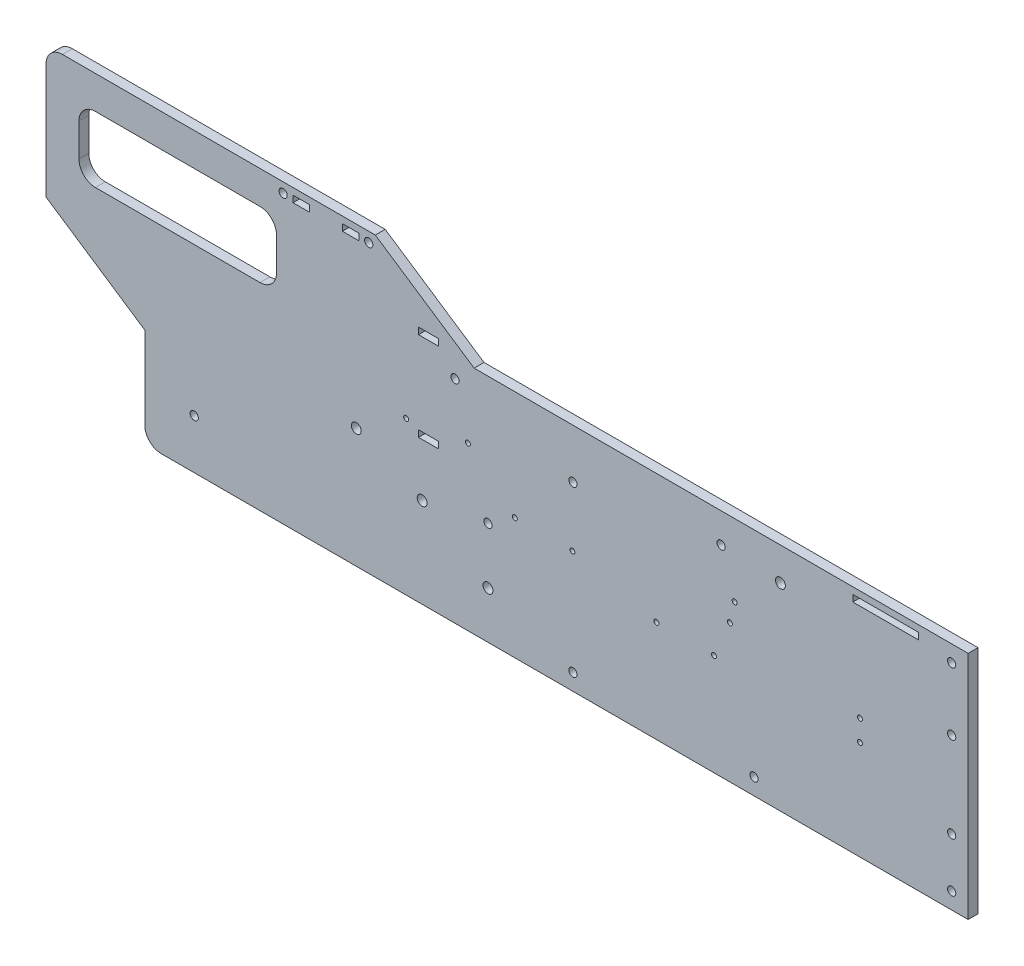
SolidWorks part; units mm, degrees
ref_plane "Front Plane" through (0, 0, 0) normal (0, 0, 1) x (1, 0, 0)
ref_plane "Top Plane" through (0, 0, 0) normal (0, 1, 0) x (1, 0, 0)
ref_plane "Right Plane" through (0, 0, 0) normal (1, 0, 0) x (0, 0, -1)
sketch "Sketch1" plane through (0, 0, 0) normal (0, 0, 1) x (1, 0, 0)
  line L0 (-211.6542, 23.1199) -> (-151.6542, 23.1199)
  line L1 (58.3458, 13.1199) -> (58.3458, -56.8801)
  line L2 (-121.6542, 33.1199) -> (-221.6542, 33.1199)
  line L3 (-221.6542, 33.1199) -> (-221.6542, -6.8801)
  line L4 (-191.6542, -56.8801) -> (58.3458, -56.8801)
  line L5 (-121.6542, 33.1199) -> (-91.6542, 13.1199)
  line L6 (-191.6542, -26.8801) -> (-191.6542, -56.8801)
  line L7 (-91.6542, 13.1199) -> (58.3458, 13.1199)
  line L8 (-211.6542, 3.1199) -> (-151.6542, 3.1199)
  line L9 (-151.6542, 3.1199) -> (-151.6542, 23.1199)
  line L10 (-211.6542, 23.1199) -> (-211.6542, 3.1199)
  line L12 (28.3458, 11.1199) -> (28.3458, 10.1199)
  line L13 (-221.6542, -6.8801) -> (-191.6542, -26.8801)
  line L14 (43.3458, 11.1199) -> (38.3458, 11.1199)
  line L15 (38.3458, 11.1199) -> (38.3458, 10.1199)
  line L16 (38.3458, 10.1199) -> (43.3458, 10.1199)
  line L17 (43.3458, 10.1199) -> (43.3458, 11.1199)
  line L18 (28.3458, 10.1199) -> (23.3458, 10.1199)
  line L19 (23.3458, 10.1199) -> (23.3458, 11.1199)
  line L20 (23.3458, 11.1199) -> (28.3458, 11.1199)
  circle A0 centre (53.3458, 7.9455) radius 1.25
  circle A1 centre (53.3458, -52.0545) radius 1.25
  circle A2 centre (25.5058, -18.3301) radius 0.75
extrude "Boss-Extrude2" add sketch "Sketch1" along normal blind 3
sketch "Sketch4" plane through (0, 0, 3) normal (0, 0, 1) x (1, 0, 0)
  circle A0 centre (-12.5542, -8.7801) radius 0.75
extrude "Cut-Extrude3" cut sketch "Sketch4" against normal blind 3
sketch "Sketch5" plane through (0, 0, 3) normal (0, 0, 1) x (1, 0, 0)
  circle A0 centre (-13.9942, -15.0201) radius 0.75
extrude "Cut-Extrude4" cut sketch "Sketch5" against normal blind 3
sketch "Sketch14" plane through (0, 0, 3) normal (0, 0, 1) x (1, 0, 0)
  circle A0 centre (25.5058, -20.3301) radius 0.75
  circle A1 centre (25.5058, -26.7301) radius 0.75
extrude "Cut-Extrude12" cut sketch "Sketch14" against normal blind 10
sketch "Sketch15" plane through (0, 0, 3) normal (0, 0, 1) x (1, 0, 0)
  circle A0 centre (25.5058, -18.3301) radius 0.75
extrude "Boss-Extrude4" add sketch "Sketch15" against normal blind 3
sketch "Sketch20" plane through (0, 0, 3) normal (0, 0, 1) x (1, 0, 0)
  circle A0 centre (-16.6542, 4.1199) radius 1.25
extrude "Cut-Extrude17" cut sketch "Sketch20" against normal blind 3
sketch "Sketch23" plane through (0, 0, 3) normal (0, 0, 1) x (1, 0, 0)
  circle A0 centre (-93.5247, -7.5214) radius 0.75
extrude "Cut-Extrude21" cut sketch "Sketch23" against normal blind 10
sketch "Sketch25" plane through (0, 0, 3) normal (0, 0, 1) x (1, 0, 0)
  line L0 (28.3458, 11.1199) -> (38.3458, 11.1199)
  line L1 (38.3458, 11.1199) -> (38.3458, 10.1199)
  line L2 (38.3458, 10.1199) -> (28.3458, 10.1199)
  line L3 (28.3458, 10.1199) -> (28.3458, 11.1199)
extrude "Cut-Extrude23" cut sketch "Sketch25" against normal blind 3
sketch "Sketch26" plane through (0, 0, 3) normal (0, 0, 1) x (1, 0, 0)
  circle A0 centre (-97.4442, 7.4199) radius 1.25
extrude "Cut-Extrude24" cut sketch "Sketch26" against normal blind 3
sketch "Sketch29" plane through (0, 0, 3) normal (0, 0, 1) x (1, 0, 0)
  circle A0 centre (-176.6542, -41.8801) radius 1.25
extrude "Cut-Extrude27" cut sketch "Sketch29" against normal blind 3
sketch "Sketch33" plane through (0, 0, 3) normal (0, 0, 1) x (1, 0, 0)
  line L3 (-126.6542, 31.1199) -> (-131.6542, 31.1199)
  line L4 (-131.6542, 31.1199) -> (-131.6542, 29.1199)
  line L5 (-131.6542, 29.1199) -> (-126.6542, 29.1199)
  line L6 (-126.6542, 29.1199) -> (-126.6542, 31.1199)
extrude "Cut-Extrude31" cut sketch "Sketch33" against normal blind 3
sketch "Sketch34" plane through (0, 0, 3) normal (0, 0, 1) x (1, 0, 0)
  line L0 (-146.6542, 31.1199) -> (-141.6542, 31.1199)
  line L1 (-146.6542, 31.1199) -> (-146.6542, 29.1199)
  line L2 (-146.6542, 29.1199) -> (-141.6542, 29.1199)
  line L3 (-141.6542, 29.1199) -> (-141.6542, 31.1199)
extrude "Cut-Extrude32" cut sketch "Sketch34" against normal blind 3
sketch "Sketch35" plane through (0, 0, 3) normal (0, 0, 1) x (1, 0, 0)
  circle A0 centre (-123.6542, 30.1199) radius 1.25
  circle A1 centre (-149.6542, 30.1199) radius 1.25
extrude "Cut-Extrude33" cut sketch "Sketch35" against normal blind 3
sketch "Sketch37" plane through (0, 0, 3) normal (0, 0, 1) x (1, 0, 0)
  circle A0 centre (-61.6542, -1.8801) radius 1.25
extrude "Cut-Extrude34" cut sketch "Sketch37" against normal blind 3
sketch "Sketch38" plane through (0, 0, 3) normal (0, 0, 1) x (1, 0, 0)
  circle A0 centre (-87.4442, -25.5801) radius 1.25
extrude "Cut-Extrude35" cut sketch "Sketch38" against normal blind 3
sketch "Sketch41" plane through (0, 0, 3) normal (0, 0, 1) x (1, 0, 0)
  circle A0 centre (-112.3061, -10.3951) radius 0.75
extrude "Cut-Extrude38" cut sketch "Sketch41" against normal blind 3
sketch "Sketch42" plane through (0, 0, 3) normal (0, 0, 1) x (1, 0, 0)
  line L0 (-108.5247, -11.5214) -> (-108.5247, -13.5214)
  line L1 (-108.5247, -13.5214) -> (-102.5247, -13.5214)
  line L2 (-102.5247, -13.5214) -> (-102.5247, -11.5214)
  line L3 (-102.5247, -11.5214) -> (-108.5247, -11.5214)
extrude "Cut-Extrude40" cut sketch "Sketch42" against normal blind 3
sketch "Sketch43" plane through (0, 0, 3) normal (0, 0, 1) x (1, 0, 0)
  line L0 (-108.5247, 15.4786) -> (-108.5247, 13.4786)
  line L1 (-108.5247, 15.4786) -> (-102.5247, 15.4786)
  line L2 (-102.5247, 15.4786) -> (-102.5247, 13.4786)
  line L3 (-102.5247, 13.4786) -> (-108.5247, 13.4786)
extrude "Cut-Extrude41" cut sketch "Sketch43" against normal blind 3
sketch "Sketch45" plane through (0, 0, 3) normal (0, 0, 1) x (1, 0, 0)
  circle A0 centre (53.3458, -52.0545) radius 1.25
extrude "Boss-Extrude5" add sketch "Sketch45" against normal blind 3
sketch "Sketch46" plane through (0, 0, 3) normal (0, 0, 1) x (1, 0, 0)
  circle A0 centre (53.3458, 7.9455) radius 1.25
extrude "Boss-Extrude6" add sketch "Sketch46" against normal blind 3
sketch "Sketch47" plane through (0, 0, 3) normal (0, 0, 1) x (1, 0, 0)
  circle A0 centre (53.3458, 8.1199) radius 1.25
extrude "Cut-Extrude42" cut sketch "Sketch47" against normal blind 3
sketch "Sketch49" plane through (0, 0, 3) normal (0, 0, 1) x (1, 0, 0)
  circle A0 centre (53.3458, -10.8801) radius 1.25
extrude "Cut-Extrude43" cut sketch "Sketch49" against normal blind 3
sketch "Sketch51" plane through (0, 0, 3) normal (0, 0, 1) x (1, 0, 0)
  circle A0 centre (53.3458, -36.8801) radius 1.25
extrude "Cut-Extrude44" cut sketch "Sketch51" against normal blind 3
sketch "Sketch52" plane through (0, 0, 3) normal (0, 0, 1) x (1, 0, 0)
  circle A0 centre (53.3458, -51.8801) radius 1.25
extrude "Cut-Extrude45" cut sketch "Sketch52" against normal blind 3
sketch "Sketch53" plane through (0, 0, 3) normal (0, 0, 1) x (1, 0, 0)
  circle A0 centre (-6.6542, -51.8801) radius 1.25
extrude "Cut-Extrude46" cut sketch "Sketch53" against normal blind 3
sketch "Sketch54" plane through (0, 0, 3) normal (0, 0, 1) x (1, 0, 0)
  circle A0 centre (-61.6542, -51.8801) radius 1.25
extrude "Cut-Extrude47" cut sketch "Sketch54" against normal blind 3
sketch "Sketch55" plane through (0, 0, 3) normal (0, 0, 1) x (1, 0, 0)
  line L0 (23.3458, 10.1199) -> (23.3458, 9.1199)
  line L1 (23.3458, 9.1199) -> (43.3458, 9.1199)
  line L2 (43.3458, 9.1199) -> (43.3458, 10.1199)
  line L3 (43.3458, 10.1199) -> (23.3458, 10.1199)
extrude "Cut-Extrude48" cut sketch "Sketch55" against normal blind 10
sketch "Sketch56" plane through (0, 0, 3) normal (0, 0, 1) x (1, 0, 0)
  circle A0 centre (-61.8042, -20.0301) radius 0.75
extrude "Cut-Extrude49" cut sketch "Sketch56" against normal blind 10
sketch "Sketch57" plane through (0, 0, 3) normal (0, 0, 1) x (1, 0, 0)
  circle A0 centre (-79.3042, -20.0301) radius 0.75
extrude "Cut-Extrude50" cut sketch "Sketch57" against normal blind 10
sketch "Sketch59" plane through (0, 0, 3) normal (0, 0, 1) x (1, 0, 0)
  circle A0 centre (-87.4442, -42.5801) radius 1.5
extrude "Cut-Extrude51" cut sketch "Sketch59" against normal blind 10
sketch "Sketch60" plane through (0, 0, 3) normal (0, 0, 1) x (1, 0, 0)
  circle A0 centre (-18.8042, -26.0301) radius 0.75
extrude "Cut-Extrude52" cut sketch "Sketch60" against normal blind 10
sketch "Sketch61" plane through (0, 0, 3) normal (0, 0, 1) x (1, 0, 0)
  circle A0 centre (-36.3042, -26.0301) radius 0.75
extrude "Cut-Extrude53" cut sketch "Sketch61" against normal blind 10
sketch "Sketch65" plane through (0, 0, 3) normal (0, 0, 1) x (1, 0, 0)
  circle A0 centre (1.3458, 3.1199) radius 1.5
extrude "Cut-Extrude55" cut sketch "Sketch65" against normal blind 10
sketch "Sketch66" plane through (0, 0, 3) normal (0, 0, 1) x (1, 0, 0)
  circle A0 centre (-107.4442, -29.5801) radius 1.5
extrude "Cut-Extrude56" cut sketch "Sketch66" against normal blind 10
sketch "Sketch67" plane through (0, 0, 3) normal (0, 0, 1) x (1, 0, 0)
  circle A0 centre (-127.4442, -20.5801) radius 1.5
extrude "Cut-Extrude57" cut sketch "Sketch67" against normal blind 10
sketch "Sketch68" plane through (0, 0, 3) normal (0, 0, 1) x (1, 0, 0)
  line L0 (-221.6542, 33.1199) -> (-216.6542, 33.1199)
  line L1 (-121.6542, 33.1199) -> (-221.6542, 33.1199) construction
  line L3 (-221.6542, 33.1199) -> (-221.6542, 28.1199)
  arc A0 (-216.6542, 33.1199) -> (-221.6542, 28.1199) centre (-216.6542, 28.1199) ccw
extrude "Cut-Extrude58" cut sketch "Sketch68" against normal blind 10
sketch "Sketch69" plane through (0, 0, 3) normal (0, 0, 1) x (1, 0, 0)
  line L0 (-191.6542, -56.8801) -> (-191.6542, -51.8801)
  line L1 (-191.6542, -26.8801) -> (-191.6542, -56.8801) construction
  line L3 (-191.6542, -56.8801) -> (-186.6542, -56.8801)
  arc A0 (-191.6542, -51.8801) -> (-186.6542, -56.8801) centre (-186.6542, -51.8801) ccw
extrude "Cut-Extrude59" cut sketch "Sketch69" against normal blind 10
sketch "Sketch72" plane through (0, 0, 3) normal (0, 0, 1) x (1, 0, 0)
  line L0 (-211.6542, 23.1199) -> (-211.6542, 18.1199)
  line L1 (-211.6542, 23.1199) -> (-211.6542, 3.1199) construction
  line L2 (-211.6542, 3.1199) -> (-211.6542, 8.1199)
  line L3 (-211.6542, 23.1199) -> (-206.6542, 23.1199)
  line L5 (-151.6542, 23.1199) -> (-156.6542, 23.1199)
  line L6 (-151.6542, 23.1199) -> (-211.6542, 23.1199) construction
  line L8 (-151.6542, 3.1199) -> (-156.6542, 3.1199)
  line L9 (-211.6542, 3.1199) -> (-151.6542, 3.1199) construction
  line L11 (-211.6542, 3.1199) -> (-206.6542, 3.1199)
  line L12 (-151.6542, 18.1199) -> (-151.6542, 23.1199)
  line L13 (-151.6542, 8.1199) -> (-151.6542, 3.1199)
  arc A0 (-206.6542, 23.1199) -> (-211.6542, 18.1199) centre (-206.6542, 18.1199) ccw
  arc A1 (-211.6542, 8.1199) -> (-206.6542, 3.1199) centre (-206.6542, 8.1199) ccw
  arc A2 (-151.6542, 18.1199) -> (-156.6542, 23.1199) centre (-156.6542, 18.1199) ccw
  arc A3 (-156.6542, 3.1199) -> (-151.6542, 8.1199) centre (-156.6542, 8.1199) ccw
extrude "Boss-Extrude7" add sketch "Sketch72" against normal blind 3
